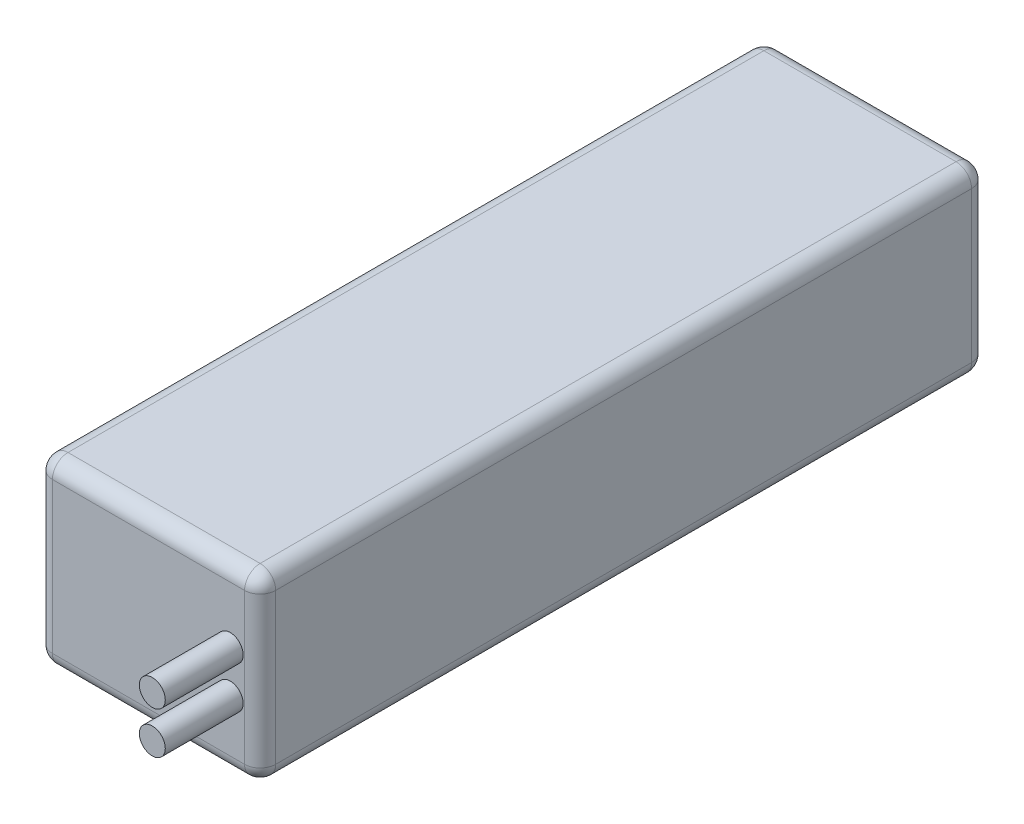
SolidWorks part; units mm, degrees
ref_plane "Спереди" through (0, 0, 0) normal (0, 0, 1) x (1, 0, 0)
ref_plane "Сверху" through (0, 0, 0) normal (0, 1, 0) x (1, 0, 0)
ref_plane "Справа" through (0, 0, 0) normal (1, 0, 0) x (0, 0, -1)
sketch "Эскиз1" plane through (0, 0, 0) normal (0, 0, 1) x (1, 0, 0)
  line L1 (-21.5, 17.5) -> (21.5, 17.5)
  line L2 (-21.5, 17.5) -> (-21.5, -17.5)
  line L3 (-21.5, -17.5) -> (21.5, -17.5)
  line L4 (21.5, 17.5) -> (21.5, -17.5)
  line L5 (-21.5, 17.5) -> (21.5, -17.5) construction
  line L6 (-21.5, -17.5) -> (21.5, 17.5) construction
  point P0 (0, 0)
  dimension "D1" = 43
  dimension "D2" = 35
extrude "Бобышка-Вытянуть1" add sketch "Эскиз1" along normal blind 140
sketch "Эскиз2" plane through (0, 0, 140) normal (0, 0, 1) x (1, 0, 0)
  line L0 (15.7347, 17.5) -> (15.7347, -17.5) construction
  line L1 (21.5, 17.5) -> (-21.5, 17.5) construction
  line L2 (-21.5, -17.5) -> (21.5, -17.5) construction
  circle A0 centre (15.7347, 3.5986) radius 2.5
  circle A1 centre (15.7347, -4.4921) radius 2.5
  dimension "D1" = 5
  dimension "D2" = 5
extrude "Бобышка-Вытянуть2" add sketch "Эскиз2" along normal blind 15
fillet "Скругление1" radius 3 12 edges at (0, -17.5, 140) (-21.5, 0, 140) (-21.5, -17.5, 70) (-21.5, 0, 0) (0, -17.5, 0) (21.5, -17.5, 70) (21.5, 0, 140) (21.5, 0, 0) (21.5, 17.5, 70) (0, 17.5, 140) (-21.5, 17.5, 70) (0, 17.5, 0)
